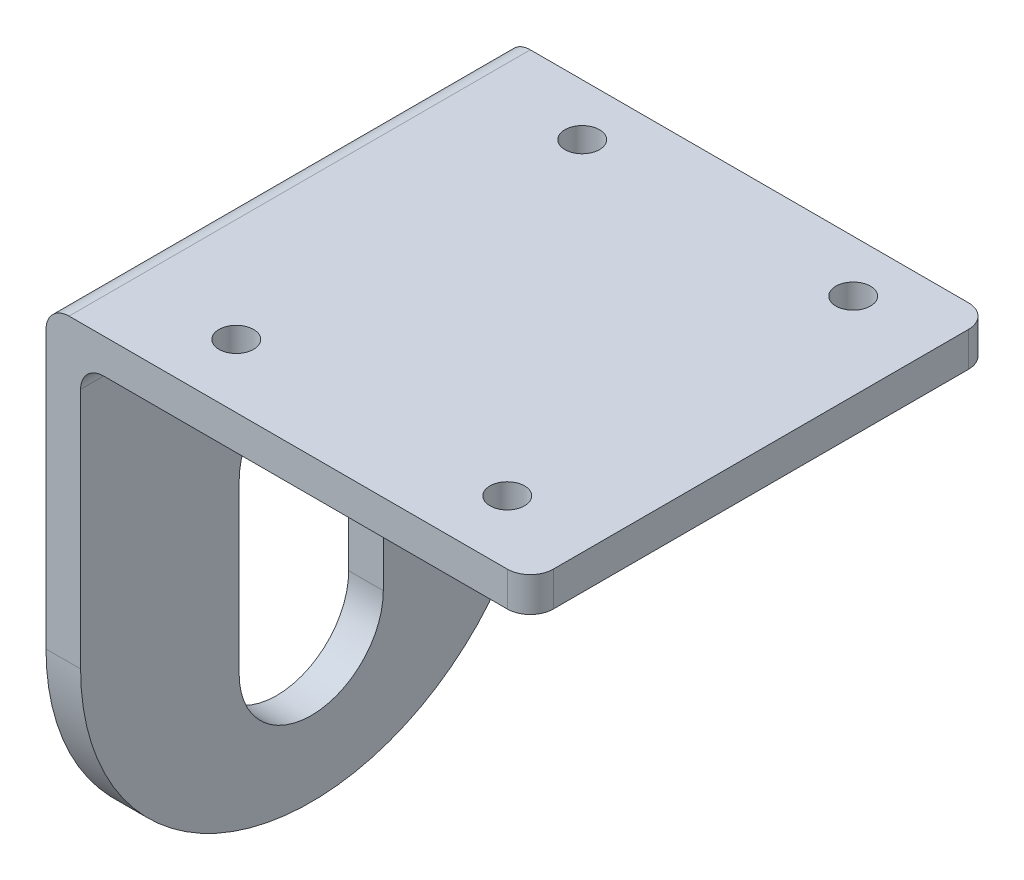
SolidWorks part; units mm, degrees
ref_plane "Front Plane" through (0, 0, 0) normal (0, 0, 1) x (1, 0, 0)
ref_plane "Top Plane" through (0, 0, 0) normal (0, 1, 0) x (1, 0, 0)
ref_plane "Right Plane" through (0, 0, 0) normal (1, 0, 0) x (0, 0, -1)
sketch "Sketch1" plane through (0, 0, 0) normal (0, 1, 0) x (1, 0, 0)
  line L0 (20.3999, -19.4284) -> (21, -20) construction
  line L1 (-19, -20) -> (19, -20)
  line L2 (-21, -18) -> (-21, 18)
  line L3 (-19, 20) -> (19, 20)
  line L4 (21, -18) -> (21, 18)
  line L6 (-19, -20) -> (-21, -20)
  line L7 (15, 15.5) -> (16.275, 15.5)
  line L8 (-19, 20) -> (-21, 20)
  line L9 (-21, 20) -> (-21, 18)
  line L10 (-21, -20) -> (-21, -18)
  circle A1 centre (13.5, 15.5) radius 1.5
  circle A2 centre (-10, 15.5) radius 1.5
  arc A3 (19, 20) -> (21, 18) centre (19, 18) cw
  arc A6 (21, -18) -> (19, -20) centre (19, -18) cw
  circle A7 centre (-10, -14.5) radius 1.5
  circle A8 centre (13.5, -14.5) radius 1.5
  point P0 (0, 0)
  point P15 (21, 20)
  dimension "D5" = 3
  dimension "D3" = 4.5
  dimension "D4" = 7.5
  dimension "D7" = 3
  dimension "D6" = 23.5
  dimension "D8" = 2
  dimension "D9" = 30
  dimension "D11" = 2
  dimension "D13" = 3
  dimension "D15" = 3
  dimension "D12" = 5.5
  dimension "D1" = 42
  dimension "D2" = 40
  dimension "D14" = 23.5
extrude "Boss-Extrude1" add sketch "Sketch1" along normal blind 3
sketch "Sketch2" plane through (-21, 0, 0) normal (-1, 0, 0) x (0, 0, 1)
  line L4 (-20, 0) -> (20, 0)
  line L5 (20, 0) -> (20, 3)
  line L6 (20, 3) -> (-20, 3)
  line L7 (-20, 3) -> (-20, 0)
  line L8 (-20, 0) -> (20, 0)
  line L9 (20, 0) -> (20, 3)
  line L10 (20, 3) -> (-20, 3)
  line L11 (-20, 3) -> (-20, 0)
  dimension "D1" = 0
extrude "Cut-Extrude1" cut sketch "Sketch2" against normal blind 3
sketch "Sketch3" plane through (-18, 0, 0) normal (-1, 0, 0) x (0, 0, 1)
  line L0 (-20, 3) -> (20, 3)
  line L1 (20, 3) -> (20, -23)
  line L3 (-20, -23) -> (-20, 3)
  line L7 (-6.25, -30.25) -> (-6.25, -15.75)
  line L9 (6.25, -30.25) -> (6.25, -15.75)
  arc A0 (-20, -23) -> (20, -23) centre (0, -23) ccw
  arc A3 (-6.25, -30.25) -> (6.25, -30.25) centre (0, -30.25) ccw
  arc A4 (6.25, -15.75) -> (-6.25, -15.75) centre (0, -15.75) ccw
  point P7 (0, -23)
extrude "Boss-Extrude2" add sketch "Sketch3" along normal blind 3
fillet "Fillet1" radius 2 1 edges at (-21, 3, 0)
fillet "Fillet2" radius 2 1 edges at (-18, 0, 0)
